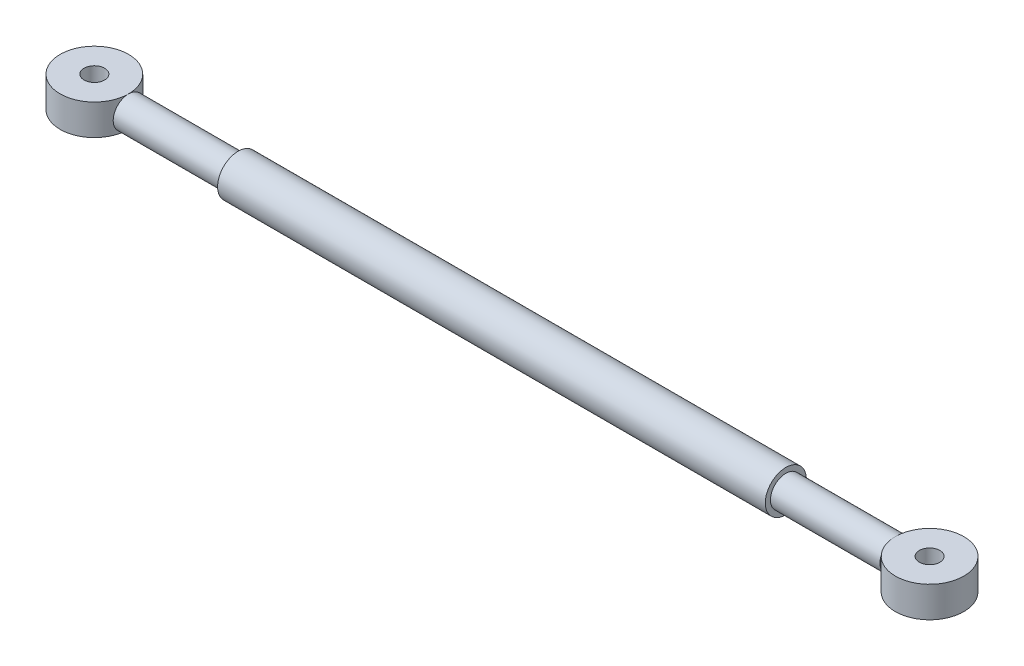
SolidWorks part; units mm, degrees
material "AISI 304"
ref_plane "前视基准面" through (0, 0, 0) normal (0, 0, 1) x (1, 0, 0)
ref_plane "上视基准面" through (0, 0, 0) normal (0, 1, 0) x (1, 0, 0)
ref_plane "右视基准面" through (0, 0, 0) normal (1, 0, 0) x (0, 0, -1)
sketch "Sketch1" plane through (0, 0, 0) normal (1, 0, 0) x (0, 0, -1)
  circle A0 centre (0, 0) radius 3
  dimension "D1" = 6
extrude "Boss-Extrude1" add sketch "Sketch1" along normal mid plane 80
sketch "Sketch2" plane through (40, 0, 0) normal (1, 0, 0) x (0, 0, -1)
  circle A0 centre (0, 0) radius 2.25
  dimension "D1" = 4.5
extrude "Boss-Extrude2" add sketch "Sketch2" along normal blind 16
sketch "Sketch4" plane through (-40, 0, 0) normal (-1, 0, 0) x (0, 0, 1)
  circle A0 centre (0, 0) radius 2.25
  dimension "D1" = 4.5
extrude "Boss-Extrude4" add sketch "Sketch4" along normal blind 16
sketch "Sketch3" plane through (0, 0, 0) normal (0, 1, 0) x (1, 0, 0)
  line L0 (56, -2.25) -> (56, 2.25) construction
  line L1 (56, -2.25) -> (56, 2.25) construction
  line L3 (-56, 2.25) -> (-56, -2.25) construction
  line L4 (-56, 2.25) -> (-56, -2.25) construction
  circle A0 centre (61, 0) radius 5
  circle A1 centre (-61, 0) radius 5
  circle A2 centre (61, 0) radius 1.5
  circle A3 centre (-61, 0) radius 1.5
  dimension "D1" = 10
  dimension "D2" = 10
  dimension "D3" = 3
  dimension "D4" = 3
extrude "Boss-Extrude3" add sketch "Sketch3" along normal mid plane 4.5 separate body
